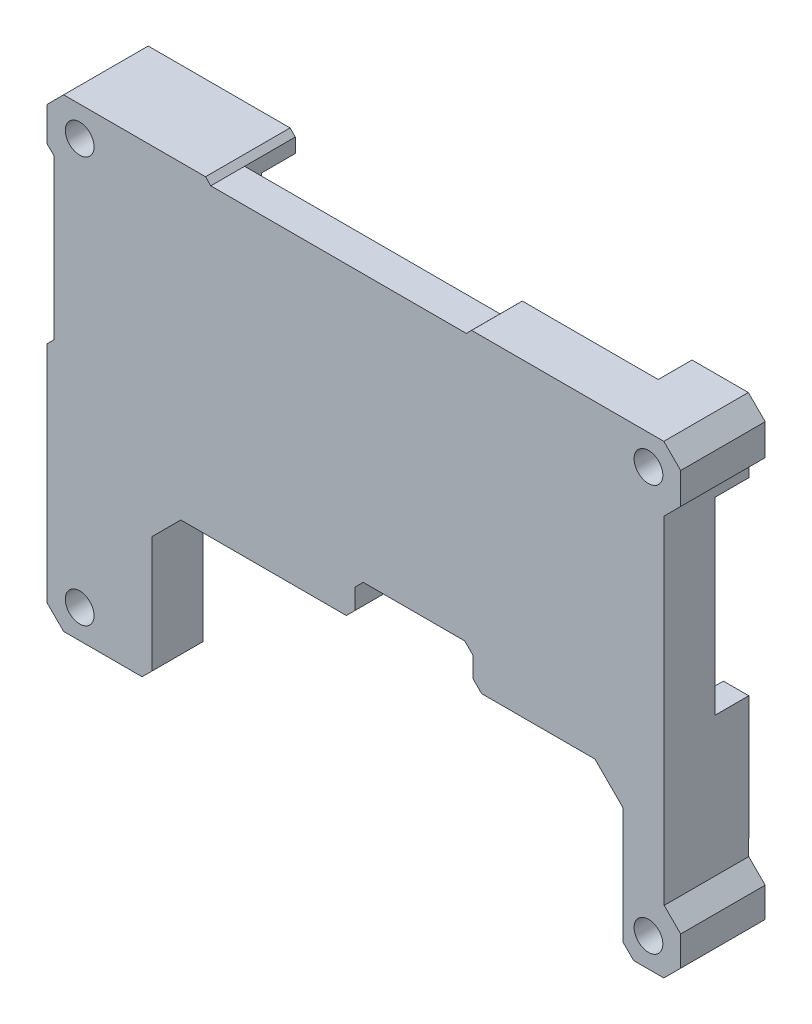
SolidWorks part; units mm, degrees
ref_plane "前视基准面" through (0, 0, 0) normal (0, 0, 1) x (1, 0, 0)
ref_plane "上视基准面" through (0, 0, 0) normal (0, 1, 0) x (1, 0, 0)
ref_plane "右视基准面" through (0, 0, 0) normal (1, 0, 0) x (0, 0, -1)
other "Configuration Table"
sketch "草图1" plane through (0, 0, 0) normal (0, 0, 1) x (1, 0, 0)
  line L1 (0, 0) -> (85, 0)
  line L2 (0, 0) -> (0, 65)
  line L3 (0, 65) -> (85, 65)
  line L4 (85, 0) -> (85, 65)
  dimension "D1" = 65
  dimension "D2" = 85
extrude "凸台-拉伸1" add sketch "草图1" along normal blind 10
sketch "草图2" plane through (0, 0, 0) normal (0, 0, -1) x (-1, 0, 0)
  circle A0 centre (-76.1669, 56.4425) radius 1.7
  circle A1 centre (-8.8888, 56.4425) radius 1.7
  circle A2 centre (-76.1669, 8.4151) radius 1.7
  circle A3 centre (-8.8888, 8.4151) radius 1.7
extrude "切除-拉伸1" cut sketch "草图2" against normal up to next
sketch "草图3" plane through (0, 0, 0) normal (0, 0, -1) x (-1, 0, 0)
  line L28 (-85, 0) -> (-85, 65) construction
  line L29 (-85, 65) -> (0, 65)
  line L30 (-85, 65) -> (-85, 0)
  line L31 (-85, 0) -> (0, 0)
  line L32 (0, 65) -> (0, 0)
  line L56 (-5, 33.4629) -> (-5.8713, 34.3342)
  line L57 (-5, 6.9926) -> (-5, 33.4629)
  line L58 (-6.9926, 5) -> (-5, 6.9926)
  line L59 (-16.2697, 5) -> (-6.9926, 5)
  line L60 (-17.4616, 6.1866) -> (-16.2697, 5)
  line L61 (-31.7436, 6.1829) -> (-17.4616, 6.1866)
  line L62 (-32.9265, 5) -> (-31.7436, 6.1829)
  line L63 (-58.7727, 5) -> (-32.9265, 5)
  line L64 (-60.0435, 6.2655) -> (-58.7727, 5)
  line L65 (-73.1524, 6.2618) -> (-60.0435, 6.2655)
  line L66 (-74.4142, 5) -> (-73.1524, 6.2618)
  line L67 (-77.9822, 5) -> (-74.4142, 5)
  line L68 (-79.9747, 6.9926) -> (-77.9822, 5)
  line L69 (-79.9747, 10.5083) -> (-79.9747, 6.9926)
  line L70 (-78.0283, 12.46) -> (-79.9747, 10.5083)
  line L71 (-78.032, 52.3531) -> (-78.0283, 12.46)
  line L72 (-79.9747, 54.2958) -> (-78.032, 52.3531)
  line L73 (-79.9747, 57.9821) -> (-79.9747, 54.2958)
  line L74 (-77.9822, 59.9747) -> (-79.9747, 57.9821)
  line L75 (-55.2451, 59.9747) -> (-77.9822, 59.9747)
  line L76 (-54.6148, 59.3497) -> (-55.2451, 59.9747)
  line L77 (-24.3949, 59.3534) -> (-54.6148, 59.3497)
  line L78 (-23.7736, 59.9747) -> (-24.3949, 59.3534)
  line L79 (-6.9926, 59.9747) -> (-23.7736, 59.9747)
  line L80 (-5, 57.9821) -> (-6.9926, 59.9747)
  line L81 (-5, 54.0174) -> (-5, 57.9821)
  line L82 (-5.875, 53.1371) -> (-5, 54.0174)
  line L83 (-5.8713, 34.3342) -> (-5.875, 53.1371)
extrude "切除-拉伸2" cut sketch "草图3" against normal up to next
sketch "草图4" plane through (0, 0, 0) normal (0, 0, -1) x (-1, 0, 0)
  line L0 (-73.1524, 6.2618) -> (-73.1524, 20.0323)
  line L1 (-73.1524, 20.0323) -> (-69.8316, 23.3532)
  line L2 (-69.8316, 23.3532) -> (-46.788, 23.3532)
  line L3 (-46.788, 23.3532) -> (-20.8513, 23.3532)
  line L4 (-20.8513, 23.3532) -> (-17.4616, 19.9634)
  line L5 (-17.4616, 19.9634) -> (-17.4616, 6.1866)
  line L6 (-31.7436, 6.1829) -> (-17.4616, 6.1866) construction
  line L7 (-17.4616, 6.1866) -> (-17.4616, 0.194)
  line L8 (-17.4616, 0.194) -> (-73.1524, 0.194)
  line L9 (-73.1524, 0.194) -> (-73.1524, 6.2618)
  line L10 (-73.1524, 6.2618) -> (-60.0435, 6.2655) construction
  point P4 (-15.5571, 6.1866)
  point P12 (-17.4616, 6.1866)
  point P13 (-73.1524, 6.2618)
  dimension "D1" = 135
  dimension "D2" = 135
extrude "切除-拉伸4" cut sketch "草图4" against normal up to next
sketch "草图5" plane through (0, 0, 0) normal (0, 0, -1) x (-1, 0, 0)
  line L0 (-24.3949, 59.3534) -> (-24.3949, 53.9064)
  line L1 (-24.3949, 53.9064) -> (-25.5261, 52.7749)
  line L2 (-25.5261, 52.7749) -> (-53.4826, 52.7749)
  line L3 (-53.4826, 52.7749) -> (-54.6142, 53.9061)
  line L4 (-54.6142, 53.9061) -> (-54.6148, 59.3497)
  line L5 (-24.3949, 59.3534) -> (-54.6148, 59.3497) construction
  line L6 (-23.7736, 59.9747) -> (-24.3949, 59.3534) construction
  line L7 (-24.3949, 59.3534) -> (-54.6148, 59.3497)
  dimension "D1" = 135
  dimension "D2" = 134.993
  dimension "D3" = 1.6
  dimension "D4" = 1.6
extrude "切除-拉伸7" cut sketch "草图5" against normal blind 6
sketch "草图6" plane through (0, 0, 0) normal (0, 0, -1) x (-1, 0, 0)
  line L0 (-5.8713, 34.3342) -> (-11.1362, 34.3342)
  line L1 (-5, 33.4629) -> (-5.8713, 34.3342) construction
  line L2 (-11.1362, 34.3342) -> (-11.6877, 35.8362)
  line L3 (-11.6877, 35.8362) -> (-11.6877, 43.8362)
  line L4 (-11.6877, 43.8362) -> (-10.2735, 45.2504)
  line L5 (-10.2735, 45.2504) -> (-5.8735, 45.2504)
  line L6 (-5.8713, 34.3342) -> (-5.875, 53.1371) construction
  line L8 (-5.8735, 45.2504) -> (-5.8713, 34.3342)
  dimension "D1" = 4.4
  dimension "D2" = 135
  dimension "D3" = 159.838
  dimension "D4" = 1.6
  dimension "D5" = 2
  dimension "D6" = 8
extrude "切除-拉伸8" cut sketch "草图6" against normal blind 6
sketch "草图7" plane through (0, 0, 0) normal (0, 0, -1) x (-1, 0, 0)
  line L0 (-76.4321, 51.2623) -> (-74.4321, 51.2623)
  line L1 (-74.4321, 51.2623) -> (-71.3195, 54.3749)
  line L2 (-71.3195, 54.3749) -> (-71.3195, 58.3749)
  line L3 (-71.3195, 58.3749) -> (-71.3195, 59.9747)
  line L4 (-76.4321, 51.2623) -> (-78.0319, 51.2623)
  line L5 (-78.0298, 28.9377) -> (-75.0298, 28.9377)
  line L6 (-75.0298, 28.9377) -> (-75.0298, 13.9377)
  line L7 (-72.9158, 11.8236) -> (-75.0298, 13.9377)
  line L8 (-24.3949, 57.6633) -> (-23.7321, 57.6633)
  line L9 (-23.7321, 57.6633) -> (-23.0617, 58.334)
  line L10 (-23.0617, 58.334) -> (-12.072, 58.334)
  line L11 (-12.072, 58.334) -> (-12.072, 55.334)
  line L12 (-12.072, 55.334) -> (-9.875, 53.1371)
  line L13 (-9.875, 53.1371) -> (-5.875, 53.1371)
  line L14 (-6.5998, 12.014) -> (-10.5998, 12.014)
  line L15 (-10.5998, 12.014) -> (-12.014, 10.5998)
  line L16 (-12.014, 10.5998) -> (-12.014, 5)
  line L17 (-6.5998, 12.014) -> (-5, 12.014)
  line L18 (-72.9158, 11.8236) -> (-73.1524, 12.0603)
  line L37 (-5.8713, 34.3342) -> (-11.1362, 34.3342)
  line L38 (-11.1362, 34.3342) -> (-11.6877, 35.8362)
  line L39 (-11.6877, 35.8362) -> (-11.6877, 43.8362)
  line L40 (-11.6877, 43.8362) -> (-10.2735, 45.2504)
  line L41 (-10.2735, 45.2504) -> (-5.8735, 45.2504)
  line L42 (-5.8735, 45.2504) -> (-5.875, 53.1371)
  line L43 (-5.875, 53.1371) -> (-5, 54.0174)
  line L44 (-5, 54.0174) -> (-5, 57.9821)
  line L45 (-5, 57.9821) -> (-6.9926, 59.9747)
  line L46 (-6.9926, 59.9747) -> (-23.7736, 59.9747)
  line L47 (-23.7736, 59.9747) -> (-24.3949, 59.3534)
  line L48 (-24.3949, 59.3534) -> (-24.3949, 53.9064)
  line L49 (-24.3949, 53.9064) -> (-25.5261, 52.7749)
  line L50 (-25.5261, 52.7749) -> (-53.4826, 52.7749)
  line L51 (-53.4826, 52.7749) -> (-54.6142, 53.9061)
  line L52 (-54.6142, 53.9061) -> (-54.6148, 59.3497)
  line L53 (-54.6148, 59.3497) -> (-55.2451, 59.9747)
  line L54 (-55.2451, 59.9747) -> (-77.9822, 59.9747)
  line L55 (-77.9822, 59.9747) -> (-79.9747, 57.9821)
  line L56 (-79.9747, 57.9821) -> (-79.9747, 54.2958)
  line L57 (-79.9747, 54.2958) -> (-78.032, 52.3531)
  line L58 (-78.032, 52.3531) -> (-78.0283, 12.46)
  line L59 (-78.0283, 12.46) -> (-79.9747, 10.5083)
  line L60 (-79.9747, 10.5083) -> (-79.9747, 6.9926)
  line L61 (-79.9747, 6.9926) -> (-77.9822, 5)
  line L62 (-77.9822, 5) -> (-74.4142, 5)
  line L63 (-74.4142, 5) -> (-73.1524, 6.2618)
  line L64 (-73.1524, 6.2618) -> (-73.1524, 20.0323)
  line L65 (-73.1524, 20.0323) -> (-69.8316, 23.3532)
  line L66 (-69.8316, 23.3532) -> (-20.8513, 23.3532)
  line L67 (-20.8513, 23.3532) -> (-17.4616, 19.9634)
  line L68 (-17.4616, 19.9634) -> (-17.4616, 6.1866)
  line L69 (-17.4616, 6.1866) -> (-16.2697, 5)
  line L70 (-16.2697, 5) -> (-6.9926, 5)
  line L71 (-6.9926, 5) -> (-5, 6.9926)
  line L72 (-5, 6.9926) -> (-5, 33.4629)
  line L73 (-5, 33.4629) -> (-5.8713, 34.3342)
  line L74 (-5.8713, 34.3342) -> (-11.1362, 34.3342)
  line L75 (-11.1362, 34.3342) -> (-11.6877, 35.8362)
  line L76 (-11.6877, 35.8362) -> (-11.6877, 43.8362)
  line L77 (-11.6877, 43.8362) -> (-10.2735, 45.2504)
  line L78 (-10.2735, 45.2504) -> (-5.8735, 45.2504)
  line L79 (-5.8735, 45.2504) -> (-5.875, 53.1371)
  line L80 (-5.875, 53.1371) -> (-5, 54.0174)
  line L81 (-5, 54.0174) -> (-5, 57.9821)
  line L82 (-5, 57.9821) -> (-6.9926, 59.9747)
  line L83 (-6.9926, 59.9747) -> (-23.7736, 59.9747)
  line L84 (-23.7736, 59.9747) -> (-24.3949, 59.3534)
  line L85 (-24.3949, 59.3534) -> (-24.3949, 53.9064)
  line L86 (-24.3949, 53.9064) -> (-25.5261, 52.7749)
  line L87 (-25.5261, 52.7749) -> (-53.4826, 52.7749)
  line L88 (-53.4826, 52.7749) -> (-54.6142, 53.9061)
  line L89 (-54.6142, 53.9061) -> (-54.6148, 59.3497)
  line L90 (-54.6148, 59.3497) -> (-55.2451, 59.9747)
  line L91 (-55.2451, 59.9747) -> (-77.9822, 59.9747)
  line L92 (-77.9822, 59.9747) -> (-79.9747, 57.9821)
  line L93 (-79.9747, 57.9821) -> (-79.9747, 54.2958)
  line L94 (-79.9747, 54.2958) -> (-78.032, 52.3531)
  line L95 (-78.032, 52.3531) -> (-78.0283, 12.46)
  line L96 (-78.0283, 12.46) -> (-79.9747, 10.5083)
  line L97 (-79.9747, 10.5083) -> (-79.9747, 6.9926)
  line L98 (-79.9747, 6.9926) -> (-77.9822, 5)
  line L99 (-77.9822, 5) -> (-74.4142, 5)
  line L100 (-74.4142, 5) -> (-73.1524, 6.2618)
  line L101 (-73.1524, 6.2618) -> (-73.1524, 20.0323)
  line L102 (-73.1524, 20.0323) -> (-69.8316, 23.3532)
  line L103 (-69.8316, 23.3532) -> (-20.8513, 23.3532)
  line L104 (-20.8513, 23.3532) -> (-17.4616, 19.9634)
  line L105 (-17.4616, 19.9634) -> (-17.4616, 6.1866)
  line L106 (-17.4616, 6.1866) -> (-16.2697, 5)
  line L107 (-16.2697, 5) -> (-6.9926, 5)
  line L108 (-6.9926, 5) -> (-5, 6.9926)
  line L109 (-5, 6.9926) -> (-5, 33.4629)
  line L110 (-5, 33.4629) -> (-5.8713, 34.3342)
  line M51 (-5.8713, 34.3342) -> (-11.1362, 34.3342)
  line M52 (-11.1362, 34.3342) -> (-11.6877, 35.8362)
  line M53 (-11.6877, 35.8362) -> (-11.6877, 43.8362)
  line M54 (-11.6877, 43.8362) -> (-10.2735, 45.2504)
  line M55 (-10.2735, 45.2504) -> (-5.8735, 45.2504)
  line M56 (-5.8735, 45.2504) -> (-5.875, 53.1371)
  line M62 (-24.3949, 59.3534) -> (-24.3949, 53.9064)
  line M63 (-24.3949, 53.9064) -> (-25.5261, 52.7749)
  line M64 (-25.5261, 52.7749) -> (-53.4826, 52.7749)
  line M65 (-53.4826, 52.7749) -> (-54.6142, 53.9061)
  line M66 (-54.6142, 53.9061) -> (-54.6148, 59.3497)
  line M67 (-54.6148, 59.3497) -> (-55.2451, 59.9747)
  line M68 (-55.2451, 59.9747) -> (-77.9822, 59.9747)
  line M72 (-78.032, 52.3531) -> (-78.0283, 12.46)
  line M78 (-73.1524, 6.2618) -> (-73.1524, 20.0323)
  line M79 (-73.1524, 20.0323) -> (-69.8316, 23.3532)
  line M80 (-69.8316, 23.3532) -> (-20.8513, 23.3532)
  line M81 (-20.8513, 23.3532) -> (-17.4616, 19.9634)
  line M82 (-17.4616, 19.9634) -> (-17.4616, 6.1866)
  line M83 (-17.4616, 6.1866) -> (-16.2697, 5)
  line M84 (-16.2697, 5) -> (-6.9926, 5)
  line M86 (-5, 6.9926) -> (-5, 33.4629)
  line M87 (-5, 33.4629) -> (-5.8713, 34.3342)
  dimension "D2" = 90
  dimension "D3" = 15
  dimension "D4" = 135
  dimension "D5" = 4
  dimension "D6" = 3
  dimension "D7" = 135
  dimension "D8" = 45
  dimension "D9" = 3
  dimension "D1" = 0
extrude "切除-拉伸11" cut sketch "草图7" against normal blind 4 contours L14 L17 L13 L12 L11 L10 L9 L8 L3 L2 L1 L0 L4 L5 L6 L7 L16 L15 M86 M87 M51 M52 M53 M54 M55 M56 M62 M63 M64 M65 M66 M67 M68 M72 M78 M79 M80 M81 M82 M83 M84
sketch "草图8" plane through (0, 0, 4) normal (0, 0, -1) x (-1, 0, 0)
  line L1 (-73.3481, 45.9587) -> (-65.3481, 45.9587)
  line L2 (-73.3481, 45.9587) -> (-73.3481, 40.9587)
  line L3 (-73.3481, 40.9587) -> (-65.3481, 40.9587)
  line L4 (-65.3481, 45.9587) -> (-65.3481, 40.9587)
  point P4 (0, 0)
  dimension "D1" = 5
  dimension "D2" = 8
extrude "切除-拉伸12" cut sketch "草图8" against normal blind 1
sketch "草图10" plane through (0, 0, 4) normal (0, 0, -1) x (-1, 0, 0)
  line L0 (-41.5465, 34.8898) -> (-37.5465, 34.8898)
  line L1 (-46.9465, 34.8898) -> (-41.5465, 34.8898)
  line L2 (-46.9465, 34.8898) -> (-46.9465, 28.8898)
  line L3 (-46.9465, 28.8898) -> (-41.5465, 28.8898)
  line L4 (-41.5465, 34.8898) -> (-41.5465, 28.8898)
  line L5 (-37.5465, 34.8898) -> (-32.1465, 34.8898)
  line L6 (-37.5465, 34.8898) -> (-37.5465, 28.8898)
  line L7 (-37.5465, 28.8898) -> (-32.1465, 28.8898)
  line L8 (-32.1465, 34.8898) -> (-32.1465, 28.8898)
  line L9 (-37.5465, 28.8898) -> (-41.5465, 28.8898)
  dimension "D1" = 5.4
  dimension "D2" = 6
  dimension "D3" = 5.4
  dimension "D4" = 4
extrude "凸台-拉伸2" add sketch "草图10" along normal up to vertex (3.04 mm away) contours L4 L1 L2 L3 | L9 L6 L0 L4 | L8 L5 L6 L7
sketch "草图11" plane through (0, 0, 4) normal (0, 0, -1) x (-1, 0, 0)
  line L1 (-40.8318, 43.6929) -> (-36.6318, 43.6929)
  line L2 (-40.8318, 43.6929) -> (-40.8318, 38.6929)
  line L3 (-40.8318, 38.6929) -> (-36.6318, 38.6929)
  line L4 (-36.6318, 43.6929) -> (-36.6318, 38.6929)
  point P4 (0, 0)
  dimension "D1" = 4.2
  dimension "D2" = 5
extrude "凸台-拉伸3" add sketch "草图11" along normal up to vertex (2.3001 mm away)
sketch "草图12" plane through (0, 0, 4) normal (0, 0, -1) x (-1, 0, 0)
  line L1 (-30.6106, 30.6859) -> (-18.6106, 30.6859)
  line L2 (-30.6106, 30.6859) -> (-30.6106, 24.6859)
  line L3 (-30.6106, 24.6859) -> (-18.6106, 24.6859)
  line L4 (-18.6106, 30.6859) -> (-18.6106, 24.6859)
  dimension "D1" = 12
  dimension "D2" = 6
extrude "凸台-拉伸4" add sketch "草图12" along normal up to vertex (2.89 mm away)
sketch "草图13" plane through (0, 0, 4) normal (0, 0, -1) x (-1, 0, 0)
  line L1 (-64.5698, 40.6188) -> (-58.0698, 40.6188)
  line L2 (-64.5698, 40.6188) -> (-64.5698, 35.5033)
  line L3 (-64.5698, 35.5033) -> (-58.0698, 35.5033)
  line L4 (-58.0698, 40.6188) -> (-58.0698, 35.5033)
  point P4 (-58.0698, 40.6188)
extrude "凸台-拉伸5" add sketch "草图13" along normal offset from surface (3.6 mm away) 0.4
sketch "草图14" plane through (0, 0, 4) normal (0, 0, -1) x (-1, 0, 0)
  line L1 (-65.7408, 30.6119) -> (-59.7408, 30.6119)
  line L2 (-65.7408, 30.6119) -> (-65.7408, 23.6119)
  line L3 (-65.7408, 23.6119) -> (-59.7408, 23.6119)
  line L4 (-59.7408, 30.6119) -> (-59.7408, 23.6119)
  dimension "D1" = 7
  dimension "D2" = 6
extrude "凸台-拉伸6" add sketch "草图14" along normal up to vertex (2.89 mm away)
sketch "草图15" plane through (0, 0, 10) normal (0, 0, 1) x (1, 0, 0)
  line L0 (69.8316, 23.3532) -> (20.8513, 23.3532) construction
  line L1 (41.4288, 23.3532) -> (55.4288, 23.3532)
  line L2 (41.4288, 23.3532) -> (41.4288, 27.7532)
  line L3 (41.4288, 27.7532) -> (55.4288, 27.7532)
  line L4 (55.4288, 23.3532) -> (55.4288, 27.7532)
  dimension "D1" = 14
  dimension "D2" = 4.4
extrude "切除-拉伸13" cut sketch "草图15" against normal up to surface (6 mm away) up to face at (69.3481, 43.4587, 4)
chamfer "倒角1" distance 1 angle 45 4 edges at (55.4288, 23.3532, 7) (55.4288, 27.7532, 7) (41.4288, 27.7532, 7) (41.4288, 23.3532, 7)
chamfer "倒角2" distance 0.6 angle 45 4 edges at (58.0698, 38.0611, 4) (61.3198, 40.6188, 4) (64.5698, 38.0611, 4) (61.3198, 35.5033, 4)
chamfer "倒角3" distance 0.6 angle 45 4 edges at (39.5465, 28.8898, 4) (32.1465, 31.8898, 4) (39.5465, 34.8898, 4) (46.9465, 31.8898, 4)
chamfer "倒角4" distance 0.6 angle 45 4 edges at (18.6106, 27.6859, 4) (24.6106, 24.6859, 4) (30.6106, 27.6859, 4) (24.6106, 30.6859, 4)
chamfer "倒角5" distance 0.6 angle 45 4 edges at (36.6318, 41.1929, 4) (38.7318, 38.6929, 4) (40.8318, 41.1929, 4) (38.7318, 43.6929, 4)
chamfer "倒角6" distance 0.6 angle 45 3 edges at (59.7408, 27.1119, 4) (62.7408, 30.6119, 4) (65.7408, 27.1119, 4)
